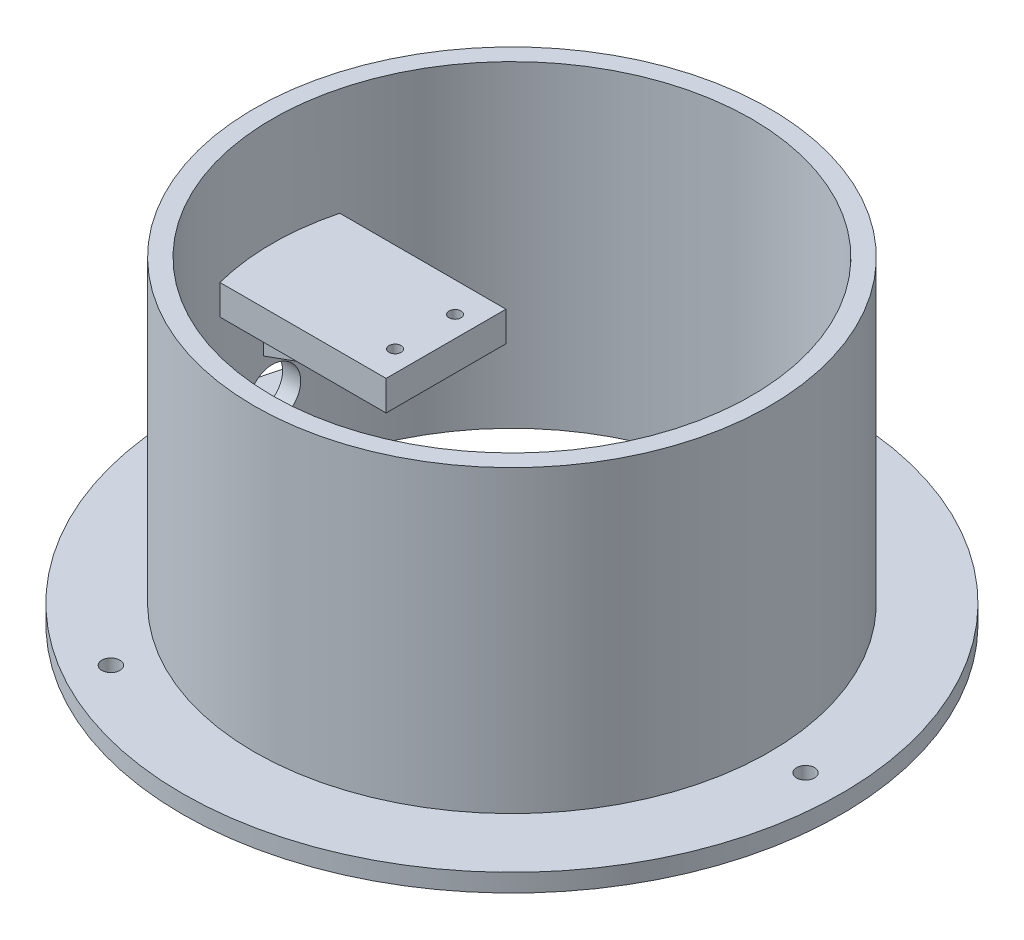
SolidWorks part; units mm, degrees
ref_plane "Front Plane" through (0, 0, 0) normal (0, 0, 1) x (1, 0, 0)
ref_plane "Top Plane" through (0, 0, 0) normal (0, 1, 0) x (1, 0, 0)
ref_plane "Right Plane" through (0, 0, 0) normal (1, 0, 0) x (0, 0, -1)
sketch "Sketch1" plane through (0, 0, 0) normal (0, 1, 0) x (1, 0, 0)
  circle A0 centre (0, 0) radius 55
extrude "Boss-Extrude1" add sketch "Sketch1" along normal blind 3
sketch "Sketch2" plane through (0, 3, 0) normal (0, 1, 0) x (1, 0, 0)
  circle A0 centre (0, 0) radius 43
extrude "Boss-Extrude2" add sketch "Sketch2" along normal blind 50
sketch "Sketch3" plane through (0, 53, 0) normal (0, 1, 0) x (1, 0, 0)
  circle A0 centre (0, 0) radius 40
extrude "Cut-Extrude1" cut sketch "Sketch3" against normal blind 66
sketch3d "3DSketch5" plane through (0, 0, 0) normal (0, 0, 1) x (1, 0, 0)
  dimension "D1" = 39
sketch "Sketch10" plane through (-39, 0, 0) normal (1, 0, 0) x (0, 0, -1)
  circle A0 centre (0, 13) radius 4.5
extrude "Cut-Extrude2" cut sketch "Sketch10" against normal blind 9
sketch3d "3DSketch6" plane through (0, 0, 0) normal (0, 0, 1) x (1, 0, 0)
  dimension "D1" = 18
sketch "Sketch12" plane through (0, 35, 0) normal (0, 1, 0) x (1, 0, 0)
  line L0 (-11, 10) -> (-39.7618, 10)
  line L10 (30, 10) -> (39.7618, 10)
  line L11 (30, 10) -> (30, -10)
  line L12 (30, -10) -> (39.7618, -10)
  line L14 (-11, -10) -> (-39.7618, -10)
  line L16 (-11, -10) -> (-11, 10)
  arc A2 (-39.7618, 10) -> (-39.7618, -10) centre (0, 0) ccw
  arc A3 (39.7618, -10) -> (39.7618, 10) centre (0, 0) ccw
extrude "Boss-Extrude4" add sketch "Sketch12" against normal blind 5
sketch "Sketch17" plane through (0, 30, 0) normal (0, -1, 0) x (1, 0, 0)
  line L0 (30, -1.5) -> (30, 1.5)
  line L1 (30, -10) -> (30, 10) construction
  line L2 (30, 1.5) -> (40.5, 1.5)
  line L3 (40.5, 1.5) -> (40.5, -1.5)
  line L4 (40.5, -1.5) -> (30, -1.5)
extrude "Boss-Extrude7" add sketch "Sketch17" along normal blind 10.5
sketch "Sketch18" plane through (0, 0, 1.5) normal (0, 0, 1) x (1, 0, 0)
  line L0 (30, 30) -> (39.9719, 19.5)
  line L1 (39.9719, 19.5) -> (30, 19.5)
  line L2 (30, 19.5) -> (30, 30)
extrude "Cut-Extrude6" cut sketch "Sketch18" against normal blind 3
sketch "Sketch19" plane through (0, 30, 0) normal (0, -1, 0) x (1, 0, 0)
  line L2 (-11, -1.5) -> (-40.5, -1.5)
  line L3 (-40.5, -1.5) -> (-40.5, 1.5)
  line L4 (-40.5, 1.5) -> (-11, 1.5)
  line L7 (-11, 1.5) -> (-11, -1.5)
extrude "Boss-Extrude8" add sketch "Sketch19" along normal blind 10.5
sketch "Sketch20" plane through (0, 0, 1.5) normal (0, 0, 1) x (1, 0, 0)
  line L3 (-39.9719, 19.5) -> (-11, 30)
  line L4 (-11, 30) -> (-11, 19.5)
  line L5 (-11, 19.5) -> (-39.9719, 19.5)
extrude "Cut-Extrude7" cut sketch "Sketch20" against normal blind 3
sketch "Sketch21" plane through (0, 3, 0) normal (0, 1, 0) x (1, 0, 0)
  circle A2 centre (49, 0) radius 1.5
extrude "Cut-Extrude8" cut sketch "Sketch21" against normal blind 8
sketch "Sketch22" plane through (0, 0, 0) normal (1, 0, 0) x (0, 0, -1)
  line L0 (0, 0) -> (0, 10.6672)
pattern_circular "CirPattern1" count 3 over 360 about axis through (0, 0, 0) along (0, 1, 0) of "Cut-Extrude8"
sketch "Sketch23" plane through (0, 35, 0) normal (0, 1, 0) x (1, 0, 0)
  circle A0 centre (-14.5, 5) radius 1
  circle A1 centre (-14.5, -5) radius 1
extrude "Cut-Extrude9" cut sketch "Sketch23" against normal blind 9
sketch "Sketch24" plane through (0, 35, 0) normal (0, 1, 0) x (1, 0, 0)
  circle A0 centre (33.5, 5) radius 1
  circle A1 centre (33.5, -5) radius 1
extrude "Cut-Extrude10" cut sketch "Sketch24" against normal blind 9
